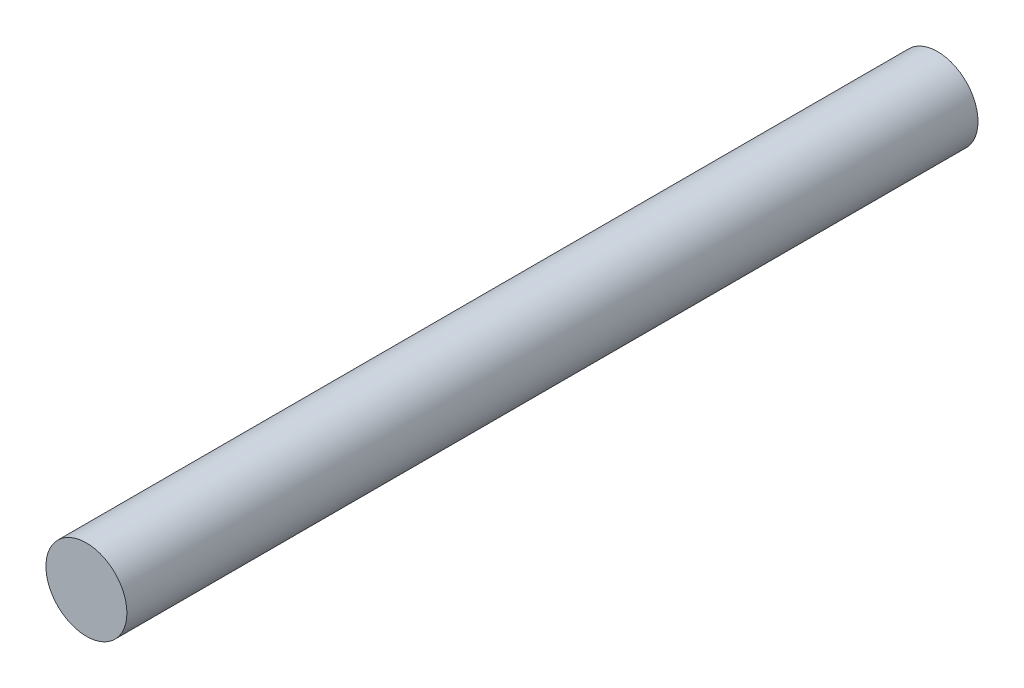
SolidWorks part; units mm, degrees
ref_plane "Piano frontale" through (0, 0, 0) normal (0, 0, 1) x (1, 0, 0)
ref_plane "Piano superiore" through (0, 0, 0) normal (0, 1, 0) x (1, 0, 0)
ref_plane "Piano destro" through (0, 0, 0) normal (1, 0, 0) x (0, 0, -1)
sketch "Schizzo1" plane through (0, 0, 0) normal (0, 0, 1) x (1, 0, 0)
  circle A0 centre (0, 0) radius 4
extrude "Estrusione-Estrusione1" add sketch "Schizzo1" along normal blind 84.09
